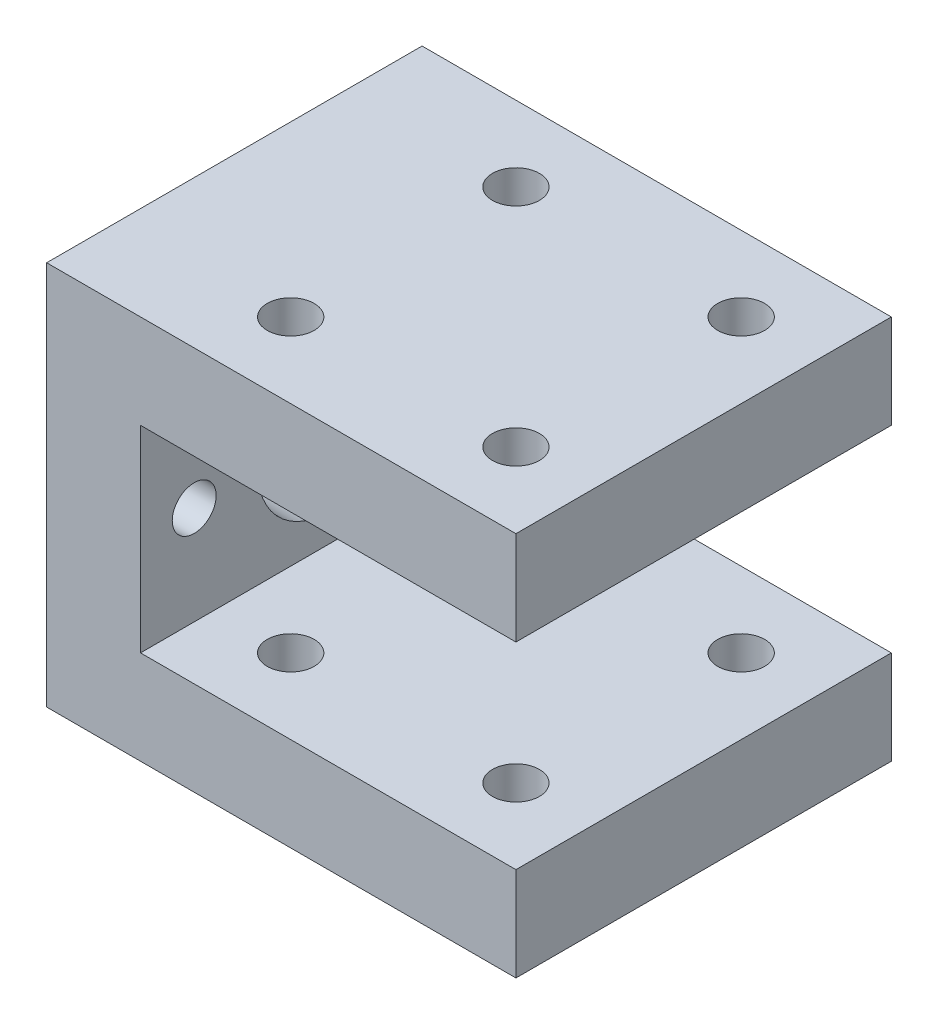
SolidWorks part; units mm, degrees
ref_plane "Front Plane" through (0, 0, 0) normal (0, 0, 1) x (1, 0, 0)
ref_plane "Top Plane" through (0, 0, 0) normal (0, 1, 0) x (1, 0, 0)
ref_plane "Right Plane" through (0, 0, 0) normal (1, 0, 0) x (0, 0, -1)
sketch "Sketch1" plane through (0, 0, 0) normal (0, 1, 0) x (1, 0, 0)
  line L1 (0, 0) -> (50, 0)
  line L2 (0, 0) -> (0, 40)
  line L3 (0, 40) -> (50, 40)
  line L4 (50, 0) -> (50, 40)
  dimension "D1" = 40
  dimension "D2" = 50
extrude "Boss-Extrude1" add sketch "Sketch1" along normal blind 10
sketch "Sketch2" plane through (0, 0, 0) normal (0, -1, 0) x (1, 0, 0)
  line L0 (50, -40) -> (0, -40) construction
  line L1 (0, 0) -> (10, 0)
  line L2 (0, 0) -> (0, -40)
  line L3 (0, -40) -> (10, -40)
  line L4 (10, 0) -> (10, -40)
  dimension "D1" = 10
extrude "Boss-Extrude2" add sketch "Sketch2" along normal blind 21
sketch "Sketch4" plane through (0, -21, 0) normal (0, -1, 0) x (1, 0, 0)
  line L1 (0, 0) -> (10, 0)
  line L2 (0, 0) -> (0, -40)
  line L3 (0, -40) -> (10, -40)
  line L4 (10, 0) -> (10, -40)
extrude "Boss-Extrude3" add sketch "Sketch4" along normal blind 10
sketch "Sketch5" plane through (10, 0, 0) normal (1, 0, 0) x (0, 0, -1)
  line L1 (0, -31) -> (40, -31)
  line L2 (0, -31) -> (0, -21)
  line L3 (0, -21) -> (40, -21)
  line L4 (40, -31) -> (40, -21)
extrude "Boss-Extrude4" add sketch "Sketch5" along normal blind 40
sketch "Sketch6" plane through (0, 0, 0) normal (-1, 0, 0) x (0, 0, 1)
  line L0 (-40, -10.5) -> (-20, -10.5)
  line L1 (-40, 10) -> (-40, -31) construction
  line L2 (-20, -10.5) -> (-17.773, -13.1777)
  line L3 (-20, -10.5) -> (-5.72, -10.5)
  line L4 (-20, -10.5) -> (-34.28, -10.5)
  circle A0 centre (-20, -10.5) radius 7.5
  circle A1 centre (-34.28, -10.5) radius 2.5
  circle A2 centre (-5.72, -10.5) radius 2.5
extrude "Cut-Extrude1" cut sketch "Sketch6" against normal blind 40
sketch "Sketch7" plane through (0, -31, 0) normal (0, -1, 0) x (1, 0, 0)
  line L0 (50, 0) -> (42, 0)
  line L1 (50, 0) -> (0, 0) construction
  line L2 (42, 0) -> (42, -8)
  line L3 (42, -8) -> (18, -8)
  line L4 (18, -8) -> (18, -32)
  line L5 (18, -32) -> (42, -32)
  circle A0 centre (18, -8) radius 2.5
  circle A1 centre (42, -8) radius 2.5
  circle A2 centre (18, -32) radius 2.5
  circle A3 centre (42, -32) radius 2.5
extrude "Cut-Extrude2" cut sketch "Sketch7" against normal through all
sketch "Sketch8" plane through (0, 0, 0) normal (-1, 0, 0) x (0, 0, 1)
  circle A0 centre (-34.28, -10.5) radius 2.34
  circle A1 centre (-5.72, -10.5) radius 2.34
  circle A2 centre (-34.28, -10.5) radius 2.5
  circle A3 centre (-5.72, -10.5) radius 2.5
  dimension "D1" = 4.68
  dimension "D2" = 4.68
extrude "Boss-Extrude5" add sketch "Sketch8" against normal blind 10
